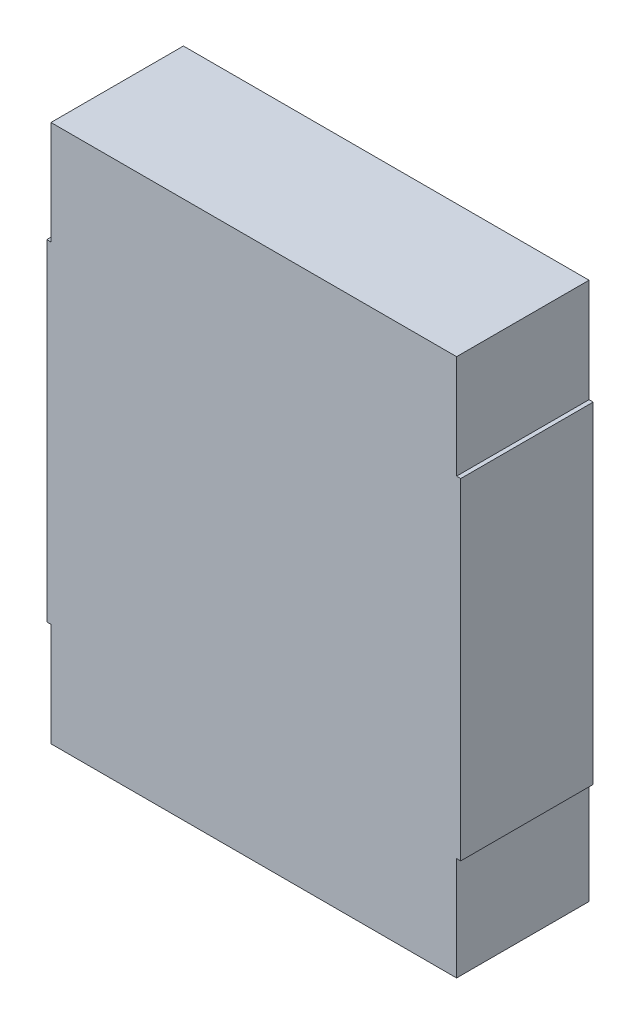
SolidWorks part; units mm, degrees
ref_plane "前视基准面" through (0, 0, 0) normal (0, 0, 1) x (1, 0, 0)
ref_plane "上视基准面" through (0, 0, 0) normal (0, 1, 0) x (1, 0, 0)
ref_plane "右视基准面" through (0, 0, 0) normal (1, 0, 0) x (0, 0, -1)
sketch "草图1" plane through (0, 0, 0) normal (0, 0, 1) x (1, 0, 0)
  line L0 (-2.5, 2) -> (-2.45, 2)
  line L1 (-2.45, 2) -> (-2.45, 3.25)
  line L2 (-2.45, 3.25) -> (2.45, 3.25)
  line L3 (2.45, 3.25) -> (2.45, 2)
  line L4 (2.45, 2) -> (2.5, 2)
  line L5 (2.5, 2) -> (2.5, -2)
  line L6 (2.5, -2) -> (2.45, -2)
  line L7 (2.45, -2) -> (2.45, -3.25)
  line L8 (2.45, -3.25) -> (-2.45, -3.25)
  line L9 (-2.45, -3.25) -> (-2.45, -2)
  line L10 (-2.45, -2) -> (-2.5, -2)
  line L11 (-2.5, -2) -> (-2.5, 2)
extrude "Component_Outline" add sketch "草图1" along normal blind 1.6 separate body
sketch3d "3D草图1"
  line L0 (0, 0, 0) -> (1, 0, 0)
  line L1 (0, 0, 0) -> (0, 1, 0)
  line L2 (0, 0, 0) -> (0, 0, 1)
  point P0 (0, 0, 0)
